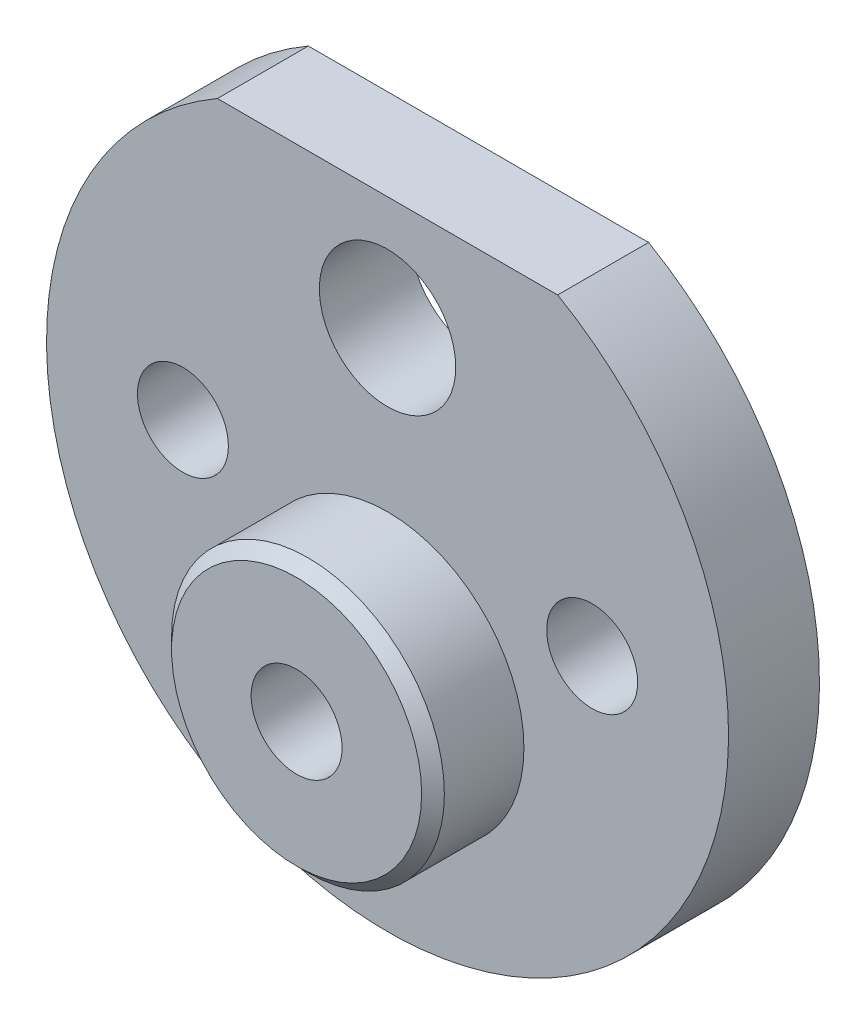
SolidWorks part; units mm, degrees
ref_plane "Front Plane" through (0, 0, 0) normal (0, 0, 1) x (1, 0, 0)
ref_plane "Top Plane" through (0, 0, 0) normal (0, 1, 0) x (1, 0, 0)
ref_plane "Right Plane" through (0, 0, 0) normal (1, 0, 0) x (0, 0, -1)
sketch "Sketch1" plane through (0, 0, 0) normal (0, 0, 1) x (1, 0, 0)
  line L0 (-7.4833, 13) -> (7.4833, 13)
  line L1 (-9, 0) -> (9, 0) construction
  line L2 (0, 0) -> (0, 8) construction
  arc A0 (-7.4833, 13) -> (7.4833, 13) centre (0, 0) ccw
  circle A1 centre (-9, 0) radius 2
  circle A2 centre (0, 8) radius 3
  circle A3 centre (9, 0) radius 2
  dimension "D1" = 30
  dimension "D3" = 4
  dimension "D4" = 4
  dimension "D5" = 6
  dimension "D2" = 13
  dimension "D6" = 9
  dimension "D7" = 9
  dimension "D8" = 8
extrude "Boss-Extrude1" add sketch "Sketch1" along normal blind 4
sketch "Sketch2" plane through (0, 0, 4) normal (0, 0, 1) x (1, 0, 0)
  circle A0 centre (0, -5) radius 6
  dimension "D1" = 12
  dimension "D2" = 5
extrude "Boss-Extrude2" add sketch "Sketch2" along normal blind 4
sketch "Sketch3" plane through (0, 0, 8) normal (0, 0, 1) x (1, 0, 0)
  circle A0 centre (0, -5) radius 2
  dimension "D1" = 4
extrude "Cut-Extrude1" cut sketch "Sketch3" against normal through all
chamfer "Chamfer1" distance 0.5 angle 45 1 edges at (6, -5, 8)
